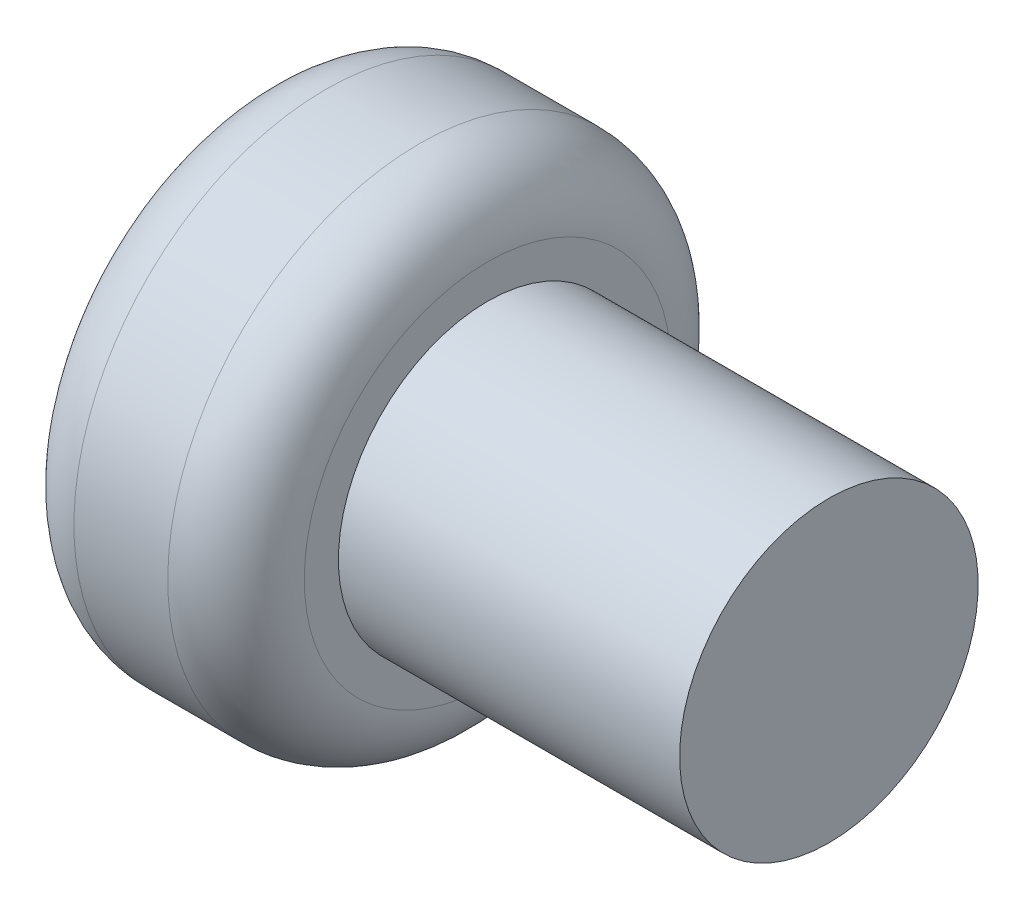
SolidWorks part; units mm, degrees
material "碳钢"
ref_plane "前视基准面" through (0, 0, 0) normal (0, 0, 1) x (1, 0, 0)
ref_plane "上视基准面" through (0, 0, 0) normal (0, 1, 0) x (1, 0, 0)
ref_plane "右视基准面" through (0, 0, 0) normal (1, 0, 0) x (0, 0, -1)
sketch "草图1" plane through (0, 0, 0) normal (0, 0, 1) x (1, 0, 0)
  line L0 (0, 0) -> (0, 2.95)
  line L1 (0, 2.95) -> (2.7, 2.95)
  line L2 (2.7, 2.95) -> (2.7, 1.75)
  line L3 (2.7, 1.75) -> (6.7, 1.75)
  line L4 (6.7, 1.75) -> (6.7, 0)
  line L5 (6.7, 0) -> (0, 0) construction
  line L6 (0, 0) -> (6.7, 0)
  dimension "D1" = 3.5
  dimension "D2" = 2.7
  dimension "D3" = 4
  dimension "D4" = 5.9
revolve "旋转1" add sketch "草图1" angle 360 about L5
cosmetic thread "装饰螺纹线1" parameters "D2"=2.85
sketch "草图2" plane through (0, 0, 0) normal (-1, 0, 0) x (0, 0, 1)
  line L1 (-2, -0.3) -> (2, -0.3)
  line L2 (-2, -0.3) -> (-2, 0.3)
  line L3 (-2, 0.3) -> (2, 0.3)
  line L4 (2, -0.3) -> (2, 0.3)
  line L5 (0, 0.3) -> (0, -0.3) construction
  line L6 (-2, 0) -> (2, 0) construction
  line L7 (-0.3, -2) -> (0.3, -2)
  line L8 (-0.3, -2) -> (-0.3, 2)
  line L9 (-0.3, 2) -> (0.3, 2)
  line L10 (0.3, -2) -> (0.3, 2)
  line L11 (0, 2) -> (0, -2) construction
  line L12 (-0.3, 0) -> (0.3, 0) construction
  point P0 (0, 0)
  point P4 (0, 0)
  dimension "D1" = 0.6
  dimension "D2" = 4
extrude "切除-拉伸1" cut sketch "草图2" against normal blind 0.5 contours L10 L1 L4 L3 | L7 L10 L1 L8 | L1 L10 L3 L8 | L3 L10 L9 L8 | L1 L8 L3 L2
fillet "圆角1" radius 0.8 2 edges at (2.7, 2.95, 0) (0, 2.95, 0)
